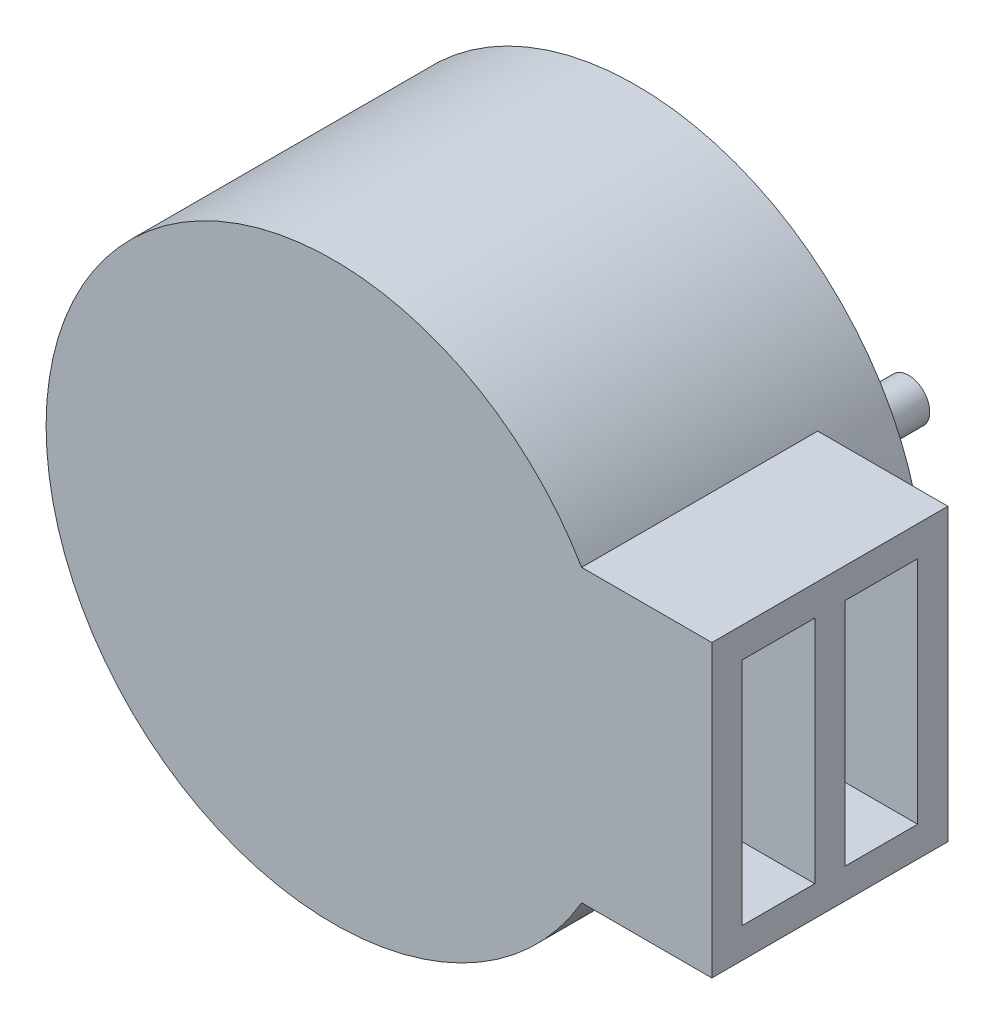
SolidWorks part; units mm, degrees
ref_plane "Front Plane" through (0, 0, 0) normal (0, 0, 1) x (1, 0, 0)
ref_plane "Top Plane" through (0, 0, 0) normal (0, 1, 0) x (1, 0, 0)
ref_plane "Right Plane" through (0, 0, 0) normal (1, 0, 0) x (0, 0, -1)
sketch "Sketch1" plane through (0, 0, 0) normal (0, 0, 1) x (1, 0, 0)
  line L0 (4.0991, 2.4) -> (6.25, 2.4)
  line L1 (6.25, 2.4) -> (6.25, -2.4)
  line L2 (6.25, -2.4) -> (4.0991, -2.4)
  line L3 (-4.75, 9.259) -> (-4.75, -9.8018) construction
  arc A0 (4.0991, -2.4) -> (4.0991, 2.4) centre (0, 0) cw
  dimension "D1" = 4.75
  dimension "D2" = 11
  dimension "D3" = 4.8
extrude "Boss-Extrude1" add sketch "Sketch1" along normal blind 5
sketch "Sketch2" plane through (0, 0, 0) normal (0, 0, -1) x (-1, 0, 0)
  line L0 (-4.0991, -2.4) -> (-6.25, -2.4) construction
  line L1 (-4.0991, -2.4) -> (-6.25, -2.4)
  line L2 (-6.25, -2.4) -> (-6.25, 2.4)
  line L3 (-6.25, 2.4) -> (-4.0991, 2.4)
  arc A0 (-4.0991, 2.4) -> (-4.0991, -2.4) centre (0, 0) ccw
extrude "Cut-Extrude1" cut sketch "Sketch2" against normal offset from surface (1.1 mm away) 3.9 up to face at (2.9623, 0, 5)
sketch "Sketch3" plane through (6.25, 0, 0) normal (1, 0, 0) x (0, 0, -1)
  line L0 (-1.1, 1.9) -> (-1.6, 1.9) construction
  line L1 (-4.5, 1.9) -> (-3.3, 1.9)
  line L2 (-4.5, 1.9) -> (-4.5, -1.9)
  line L3 (-4.5, -1.9) -> (-3.3, -1.9)
  line L4 (-3.3, 1.9) -> (-3.3, -1.9)
  line L5 (-2.8, 1.9) -> (-1.6, 1.9)
  line L6 (-2.8, 1.9) -> (-2.8, -1.9)
  line L7 (-2.8, -1.9) -> (-1.6, -1.9)
  line L8 (-1.6, 1.9) -> (-1.6, -1.9)
  line L9 (-1.1, -2.4) -> (-1.1, 2.4) construction
  line L10 (-2.8, 1.9) -> (-3.3, 1.9) construction
  line L11 (-4.5, 1.9) -> (-5, 1.9) construction
  line L12 (-5, -2.4) -> (-5, 2.4) construction
  line L13 (-4.5, 1.9) -> (-4.5, 2.4) construction
  line L14 (-5, 2.4) -> (-1.1, 2.4) construction
  line L15 (-4.5, -1.9) -> (-4.5, -2.4) construction
  line L16 (-5, -2.4) -> (-1.1, -2.4) construction
  dimension "D1" = 0.5
extrude "Cut-Extrude2" cut sketch "Sketch3" against normal blind 4
sketch "Sketch4" plane through (0, 0, 0) normal (0, 0, -1) x (-1, 0, 0)
  line L0 (-2, 0) -> (0, 0) construction
  line L1 (0, 0) -> (0, 2.7405) construction
  circle A0 centre (-2, 0) radius 0.35
  circle A1 centre (2, 0) radius 0.35
  dimension "D2" = 0.7
  dimension "D1" = 2
extrude "Boss-Extrude2" add sketch "Sketch4" along normal blind 2.5
